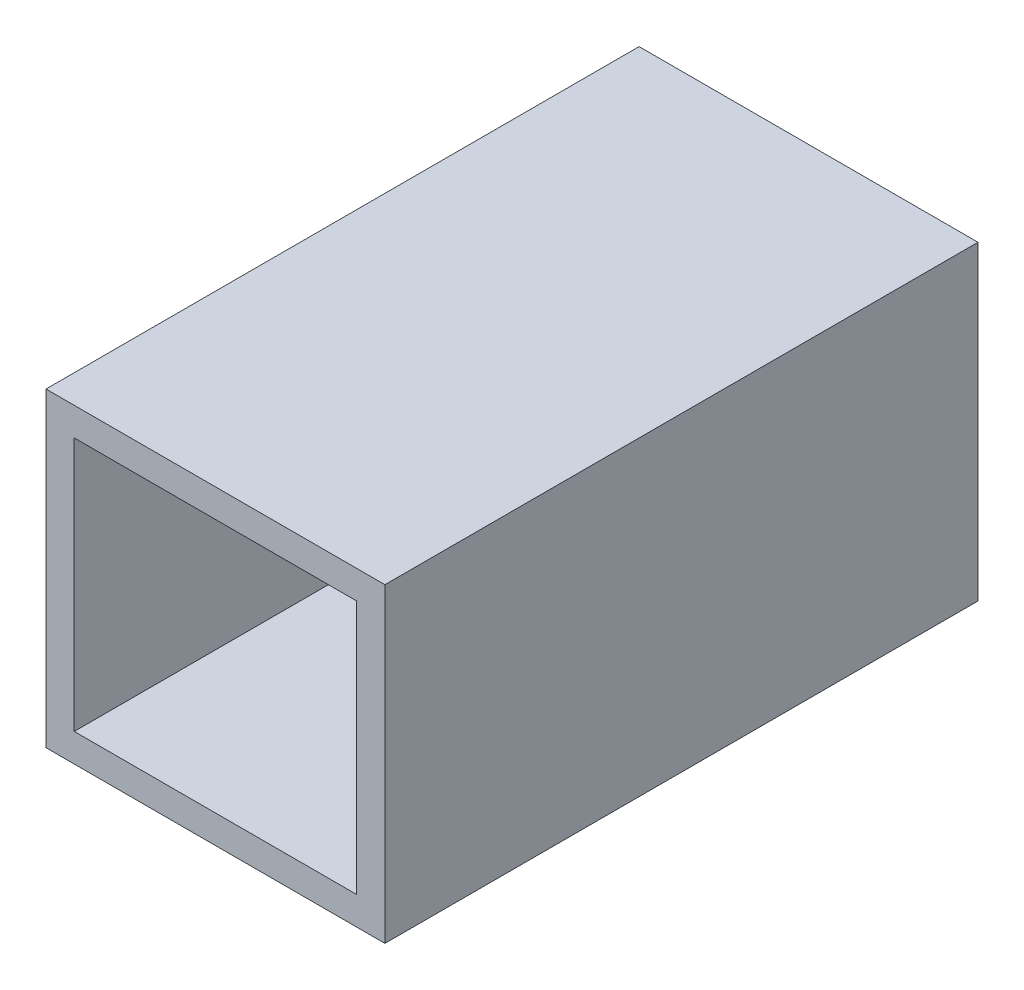
SolidWorks part; units mm, degrees
ref_plane "Front Plane" through (0, 0, 0) normal (0, 0, 1) x (1, 0, 0)
ref_plane "Top Plane" through (0, 0, 0) normal (0, 1, 0) x (1, 0, 0)
ref_plane "Right Plane" through (0, 0, 0) normal (1, 0, 0) x (0, 0, -1)
sketch "Sketch3" plane through (0, 0, 0) normal (0, 0, 1) x (1, 0, 0)
  line L0 (25, -22.5) -> (-25, -22.5)
  line L1 (30, -27.5) -> (-30, -27.5)
  line L2 (30, -27.5) -> (30, 27.5)
  line L3 (30, 27.5) -> (-30, 27.5)
  line L4 (-30, -27.5) -> (-30, 27.5)
  line L5 (30, -27.5) -> (-30, 27.5) construction
  line L6 (30, 27.5) -> (-30, -27.5) construction
  line L7 (-25, -22.5) -> (-25, 22.5)
  line L8 (25, 22.5) -> (-25, 22.5)
  line L9 (25, -22.5) -> (25, 22.5)
  point P0 (0, 0)
  dimension "D1" = 55
  dimension "D2" = 60
  dimension "D3" = 5
extrude "Boss-Extrude1" add sketch "Sketch3" against normal blind 105
sketch "Sketch6" plane through (0, -22.5, 0) normal (0, 1, 0) x (1, 0, 0)
  line L0 (25, 105) -> (25, 0) construction
  line L1 (-25, 105) -> (25, 105)
  line L2 (-25, 105) -> (-25, 100)
  line L3 (-25, 100) -> (25, 100)
  line L4 (25, 105) -> (25, 100)
  dimension "D1" = 5
extrude "Boss-Extrude3" add sketch "Sketch6" along normal blind 10
sketch "Sketch7" plane through (0, -27.5, 0) normal (0, -1, 0) x (1, 0, 0)
  line L0 (-30, 0) -> (30, -105) construction
  line L1 (30, -105) -> (30, 0) construction
  line L2 (30, 0) -> (-30, -105) construction
  circle A0 centre (0, -52.5) radius 2.5
  dimension "D1" = 5
extrude "Boss-Extrude4" add sketch "Sketch7" along normal blind 10
